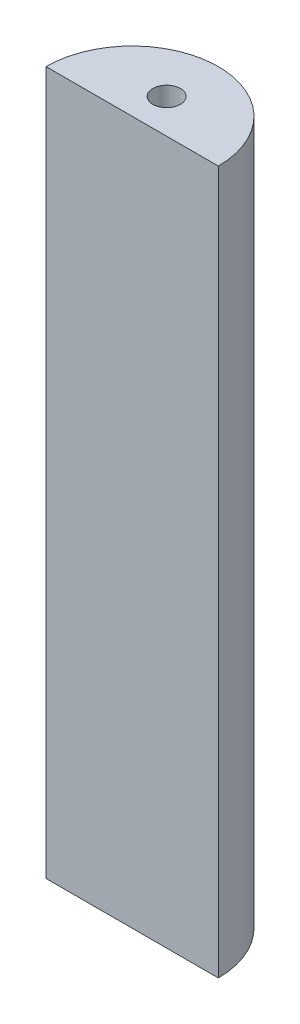
SolidWorks part; units mm, degrees
ref_plane "Ön Düzlem" through (0, 0, 0) normal (0, 0, 1) x (1, 0, 0)
ref_plane "Üst Düzlem" through (0, 0, 0) normal (0, 1, 0) x (1, 0, 0)
ref_plane "Sağ Düzlem" through (0, 0, 0) normal (1, 0, 0) x (0, 0, -1)
sketch "Çizim2" plane through (0, 0, 0) normal (0, 1, 0) x (1, 0, 0)
  line L0 (-6.25, 0) -> (6.25, 0)
  line L1 (0, 0) -> (0, 7.4047) construction
  arc A0 (6.25, 0) -> (-6.25, 0) centre (0, 0) ccw
  circle A1 centre (0, 2.5) radius 1
  dimension "D1" = 12.5
  dimension "D2" = 2
  dimension "D3" = 2.5
extrude "Yükseklik-Ekstrüzyon1" add sketch "Çizim2" along normal blind 51
